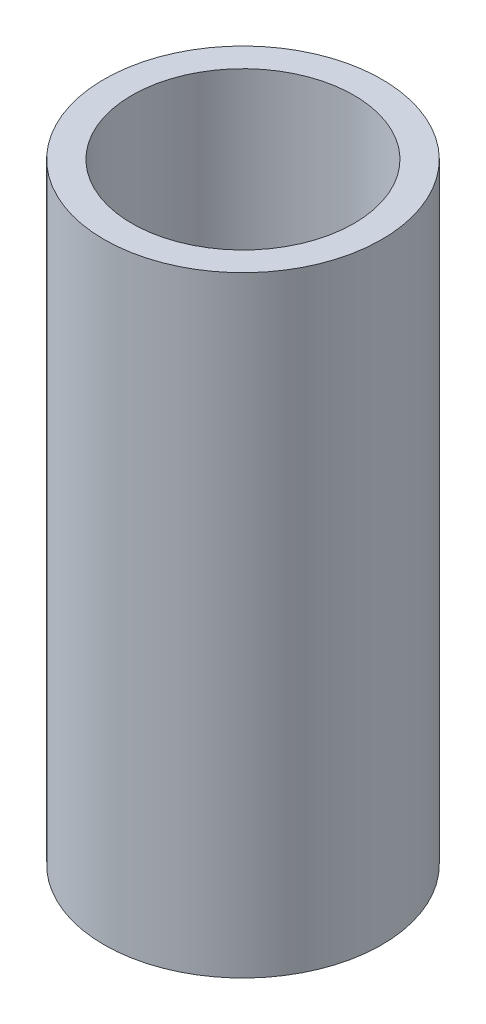
SolidWorks part; units mm, degrees
ref_plane "前视基准面" through (0, 0, 0) normal (0, 0, 1) x (1, 0, 0)
ref_plane "上视基准面" through (0, 0, 0) normal (0, 1, 0) x (1, 0, 0)
ref_plane "右视基准面" through (0, 0, 0) normal (1, 0, 0) x (0, 0, -1)
sketch "草图1" plane through (0, 0, 0) normal (0, 1, 0) x (1, 0, 0)
  circle A0 centre (0, 0) radius 10
  dimension "D1" = 20
extrude "拉伸-薄壁1" add sketch "草图1" along normal blind 44 thin thin type one direction reverse wall 2
